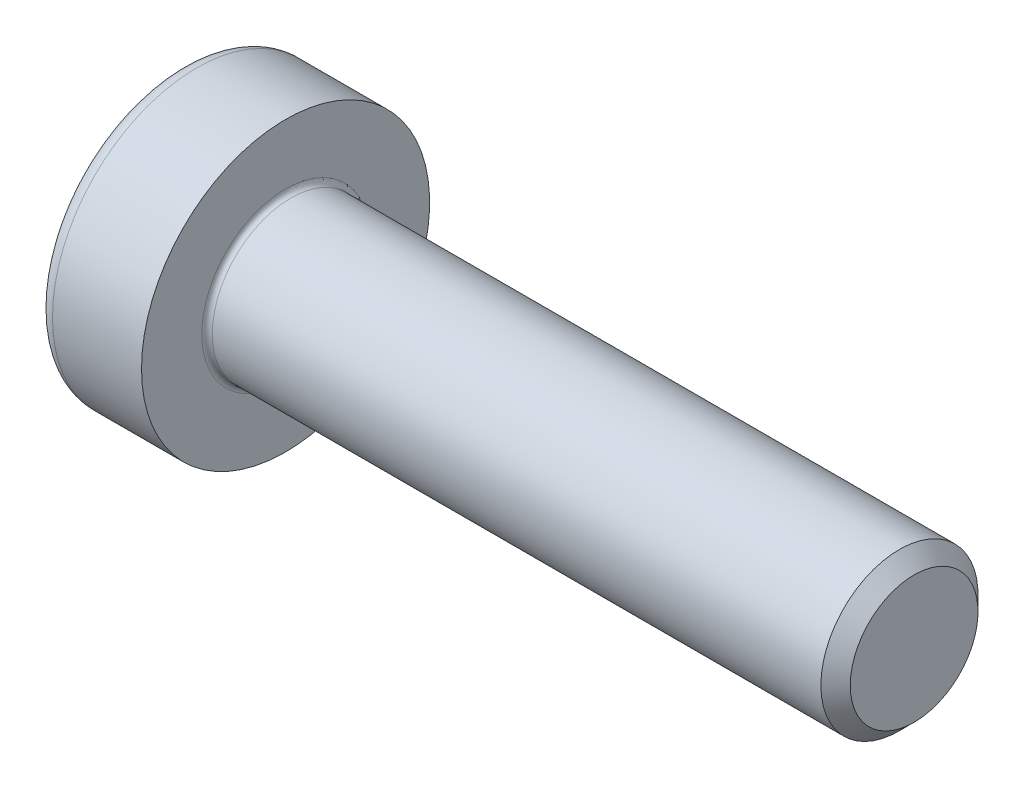
SolidWorks part; units mm, degrees
revolve "Base-Revolve" add sketch "BodySke"
sketch "BodySke" plane through (0, 0, 0) normal (0, 0, 1) x (1, 0, 0)
  line L0 (0, 0) -> (0, 2.75)
  line L1 (0, 2.75) -> (2, 2.75)
  line L2 (2, 2.75) -> (2, 1.5)
  line L3 (2, 1.5) -> (13.7195, 1.5)
  line L4 (14, 1.2195) -> (14, 0)
  line L5 (14, 0) -> (0, 0)
  line L6 (-31.75, 0) -> (127, 0) construction
  line L8 (14, 1.2195) -> (13.7195, 1.5)
  line L10 (14, -1.2195) -> (13.7195, -1.5) construction
  line L11 (2.5, 4.525) -> (2.5, -1.825) construction
  line L12 (3.5, 4.525) -> (3.5, -1.825) construction
  line L13 (-46, 4.525) -> (-46, -1.825) construction
  dimension "Head_ht" = 2
  dimension "Length" = 12
  dimension "Body_ch_ang" = 45
  dimension "Diameter" = 3
  dimension "Minor_dia" = 2.439
  dimension "Advance" = 0.5
  dimension "Thread_nom" = 10.5
  dimension "Thread_length" = 60
  dimension "Head_dia" = 5.5
cosmetic thread "ThreadCosmetic" [suppressed]
fillet "Fillet1" radius 0.1 1 edges at (2, 0, 1.5)
fillet "Fillet2" radius 0.3 1 edges at (0, 0, 2.75)
ref_plane "Plane1" through (0, 0, 0) normal (0, 0, 1) x (1, 0, 0)
ref_plane "Plane2" through (0, 0, 0) normal (0, 1, 0) x (1, 0, 0)
ref_plane "Plane3" through (0, 0, 0) normal (1, 0, 0) x (0, 0, -1)
sketch "Sketch2" plane through (0, 0, 0) normal (0, 0, 1) x (1, 0, 0)
  line L0 (0, 1) -> (1.5, 1)
  line L1 (1.5, 1) -> (2.0774, 0)
  line L2 (-31.75, 0) -> (127, 0) construction
  line L3 (2.0774, 0) -> (0, 0)
  line L4 (0, 0) -> (0, 1)
  line L6 (0, 0) -> (47.625, 0) construction
  dimension "D1" = 1
  dimension "D2" = 60
  dimension "Depth" = 1.5
revolve "Hex-PreBroach" cut sketch "Sketch2" angle 360 about L6
sketch "Sketch3" plane through (0, 0, 0) normal (-1, 0, 0) x (0, 0.5, 0.866)
  line L0 (0.5774, 1) -> (-0.5774, 1)
  line L1 (-0.5774, 1) -> (-1.1547, 0)
  line L2 (0.5774, 1) -> (1.1547, 0)
  line L3 (0.5774, -1) -> (1.1547, 0)
  line L4 (0.5774, -1) -> (-0.5774, -1)
  line L5 (-0.5774, -1) -> (-1.1547, 0)
  dimension "D1" = 1
  dimension "D2" = 1
  dimension "Hex_size" = 2
extrude "Hex" cut sketch "Sketch3" against normal blind 1.5
sketch "ThdSchSke" plane through (0, 0, 0) normal (0, 0, 1) x (1, 0, 0)
  line L0 (3.5, -1.2195) -> (3.3036, -1.5)
  line L1 (3.5, -1.2195) -> (3.6964, -1.5)
  line L2 (3.6964, -1.5) -> (3.6964, -1.875)
  line L3 (-3.175, 0) -> (5.1513, 0) construction
  line L4 (0, 2.45) -> (0, -2.45) construction
  line L5 (3.6964, -1.875) -> (3.3036, -1.875)
  line L6 (3.3036, -1.875) -> (3.3036, -1.5)
  dimension "Thread_minor" = 2.439
  dimension "Diameter" = 3
  dimension "Start" = 3.5
revolve "ThreadSchematic" [suppressed] cut sketch "ThdSchSke" angle 360 about L3
pattern_linear "ThdSchPat" [suppressed]
equation "\"D2@Sketch3\" = \"Hex_size@Sketch3\" / 2"
equation "\"D1@Sketch3\" = \"Hex_size@Sketch3\" / 2"
equation "\"D1@Sketch2\" = \"Hex_size@Sketch3\" / 2"
equation "\"Thread_minor@ThreadCosmetic\"  =  \"Minor_dia@BodySke\""
equation "\"Depth@Sketch2\" =  \"Key_eng@Hex\""
equation "\"Thread_length@ThreadCosmetic\" = ((sgn( (\"Length@BodySke\" - \"Advance@BodySke\" * 3.0) - \"Thread_nom@BodySke\" )-1)*( (\"Length@BodySke\" - \"Advance@BodySke\" * 3.0) - \"Thread_nom@BodySke\" ))/-2+ \"Thread_nom@BodySke\""
equation "\"Thread_minor@ThdSchSke\" = \"Minor_dia@BodySke\""
equation "\"Diameter@ThdSchSke\" = \"Diameter@BodySke\""
equation "\"Overcut@ThdSchSke\" = \"Diameter@BodySke\" * 1.25"
equation "\"Start@ThdSchSke\" = \"Head_ht@BodySke\" + \"Length@BodySke\" - \"Thread_length@ThreadCosmetic\"  '---Non-countersunk---"
equation "\"Num_threads@ThdSchPat\" = int( \"Thread_length@ThreadCosmetic\" / \"Advance@BodySke\" + 0.999 )  + 1"
equation "\"Advance@ThdSchPat\" = \"Thread_length@ThreadCosmetic\" /  (\"Num_threads@ThdSchPat\" - 1) 'relax it"
equation "\"Num_threads@ThdSchPat\" = \"Num_threads@ThdSchPat\" - sgn( \"Num_threads@ThdSchPat\" - 1) '---chamfered tips only---"
